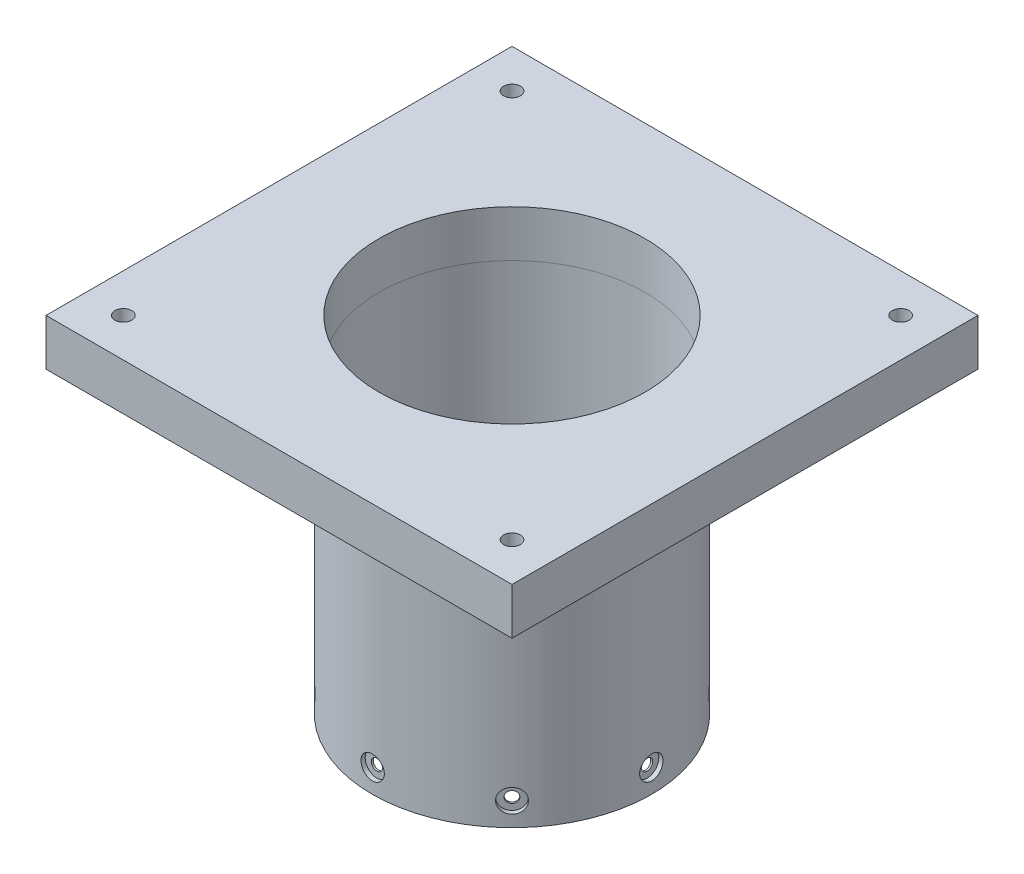
SolidWorks part; units mm, degrees
ref_plane "정면" through (0, 0, 0) normal (0, 0, 1) x (1, 0, 0)
ref_plane "윗면" through (0, 0, 0) normal (0, 1, 0) x (1, 0, 0)
ref_plane "우측면" through (0, 0, 0) normal (1, 0, 0) x (0, 0, -1)
sketch "스케치1" plane through (0, 0, 0) normal (0, 1, 0) x (1, 0, 0)
  circle A0 centre (0, 0) radius 30
  circle A1 centre (0, 0) radius 28.6
  dimension "D1" = 60
  dimension "D2" = 1.4
extrude "보스-돌출1" add sketch "스케치1" along normal blind 64
ref_plane "평면1" through (-30, 0, 0) normal (-1, 0, 0) x (0, 0, 1)
sketch "스케치7" plane through (-30, 0, 0) normal (-1, 0, 0) x (0, 0, 1)
  point P0 (0, 5)
  dimension "D1" = 5
hole_wizard "M2 남비 머리 나사용 카운터보어1" positions "스케치8" profile "스케치9" counterbore size "M2" standard "ISO"
sketch "스케치8" plane through (-30, 0, 0) normal (-1, 0, 0) x (0, 0, 1)
  point P0 (0, 5)
sketch "스케치9" plane through (-30, 5, 0) normal (0, 1, 0) x (0, 0, 1)
  line L0 (0, 0) -> (0, 10.721)
  line L1 (0, 10.721) -> (1.2, 10)
  line L2 (1.2, 10) -> (1.2, 1)
  line L3 (1.2, 1) -> (2.5, 1)
  line L4 (2.5, 1) -> (2.5, 0)
  line L5 (2.5, 0) -> (0, 0)
  line L10 (0, 10.721) -> (-1.2, 10) construction
  line L11 (0, -6.35) -> (0, 107.95) construction
  dimension "구멍 지름" = 2.4
  dimension "구멍 깊이" = 10
  dimension "카운터보어 지름" = 5
  dimension "카운터보어 깊이" = 1
  dimension "드릴 각도" = 118
pattern_circular "원형 패턴1" count 8 over 360 about axis through (0, 0, 0) along (0, 1, 0) of "M2 남비 머리 나사용 카운터보어1"
ref_plane "평면2" through (0, 64, 0) normal (0, 1, 0) x (1, 0, 0)
sketch "스케치10" plane through (0, 64, 0) normal (0, 1, 0) x (1, 0, 0)
  line L1 (50, 50) -> (-50, 50)
  line L2 (50, 50) -> (50, -50)
  line L3 (50, -50) -> (-50, -50)
  line L4 (-50, 50) -> (-50, -50)
  line L5 (50, 50) -> (-50, -50) construction
  line L6 (50, -50) -> (-50, 50) construction
  line L7 (-50, -50) -> (-41.7, -50)
  line L8 (-50, -50) -> (-50, -41.7)
  line L9 (-50, -41.7) -> (-41.7, -41.7) construction
  line L10 (-41.7, -50) -> (-41.7, -41.7) construction
  circle A0 centre (0, 0) radius 28.5599
  circle A2 centre (-41.7, -41.7) radius 1.8
  circle A3 centre (-41.7, 41.7) radius 1.8
  circle A4 centre (41.7, 41.7) radius 1.8
  circle A5 centre (41.7, -41.7) radius 1.8
  point P20 (0, 0)
  dimension "D1" = 100
  dimension "D3" = 4
  dimension "D2" = 100
extrude "보스-돌출2" add sketch "스케치10" along normal blind 10 contours L1 L4 L3 L2 A5 A4 A3 A2 A0
